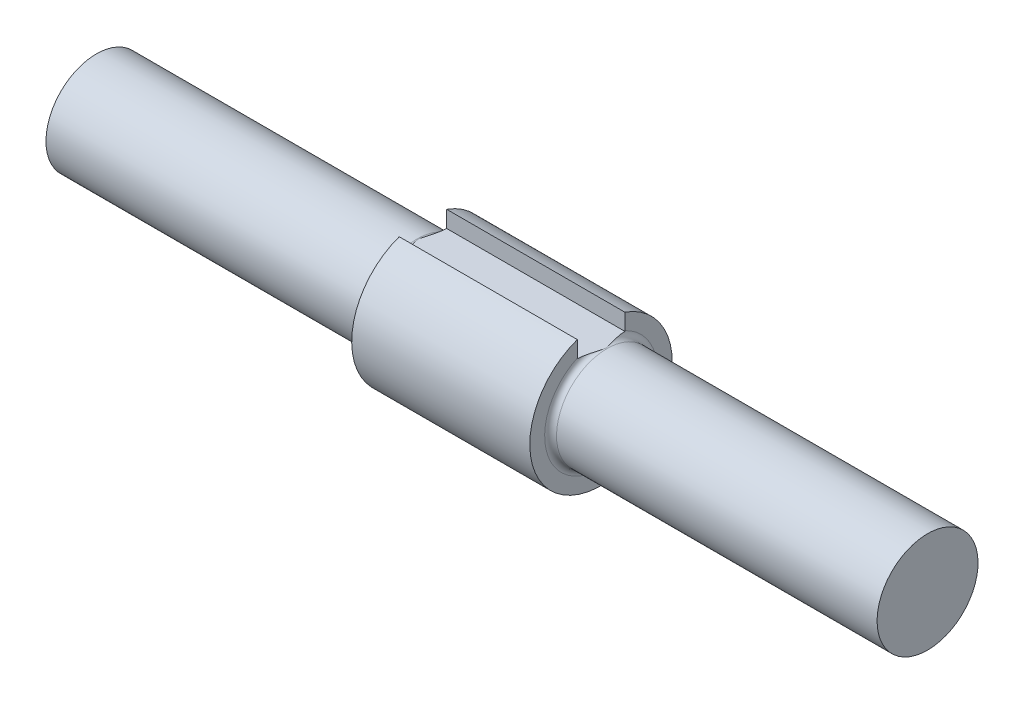
SolidWorks part; units mm, degrees
ref_plane "Front Plane" through (0, 0, 0) normal (0, 0, 1) x (1, 0, 0)
ref_plane "Top Plane" through (0, 0, 0) normal (0, 1, 0) x (1, 0, 0)
ref_plane "Right Plane" through (0, 0, 0) normal (1, 0, 0) x (0, 0, -1)
sketch "Sketch1" plane through (0, 0, 0) normal (0, 0, 1) x (1, 0, 0)
  line L0 (0, 0) -> (55, 0)
  line L1 (55, 0) -> (55, 8.5)
  line L2 (55, 8.5) -> (1, 8.5)
  line L3 (0, 9.5) -> (0, 12)
  line L4 (0, 12) -> (-30, 12)
  line L5 (-30, 12) -> (-30, 9.5)
  line L6 (-31, 8.5) -> (-85, 8.5)
  line L7 (-85, 8.5) -> (-85, 0)
  line L8 (-85, 0) -> (0, 0)
  line L9 (0, 0) -> (0, 0.1759)
  arc A0 (0, 9.5) -> (1, 8.5) centre (1, 9.5) ccw
  arc A1 (-31, 8.5) -> (-30, 9.5) centre (-31, 9.5) ccw
  point P13 (0, 8.5)
  point P16 (-30, 8.5)
  dimension "D8" = 1
  dimension "D9" = 1
  dimension "D1" = 30
  dimension "D3" = 55
  dimension "D4" = 55
  dimension "D5" = 8.5
  dimension "D6" = 12
  dimension "D7" = 8.5
revolve "Revolve1" add sketch "Sketch1" angle 360 about L8
sketch "Sketch3" plane through (0, 0, 0) normal (1, 0, 0) x (0, 0, -1)
  line L0 (0, 0) -> (0, 12)
  line L1 (0, 11.3137) -> (4, 11.3137)
  line L2 (4, 11.3137) -> (4, 8.5137)
  line L3 (4, 8.5137) -> (0, 8.5137)
  line L4 (0, 11.3137) -> (-4, 11.3137)
  line L5 (-4, 11.3137) -> (-4, 8.5137)
  line L6 (-4, 8.5137) -> (0, 8.5137)
  circle A0 centre (0, 0) radius 12 construction
  circle A1 centre (0, 0) radius 12
  dimension "D1" = 4
  dimension "D2" = 2.8
extrude "Cut-Extrude2" cut sketch "Sketch3" against normal through all and the other way through all contours L3 L2 L1 L0 | L5 L6 L0 L4 | L0 A1 L4 | L1 A1 L0
